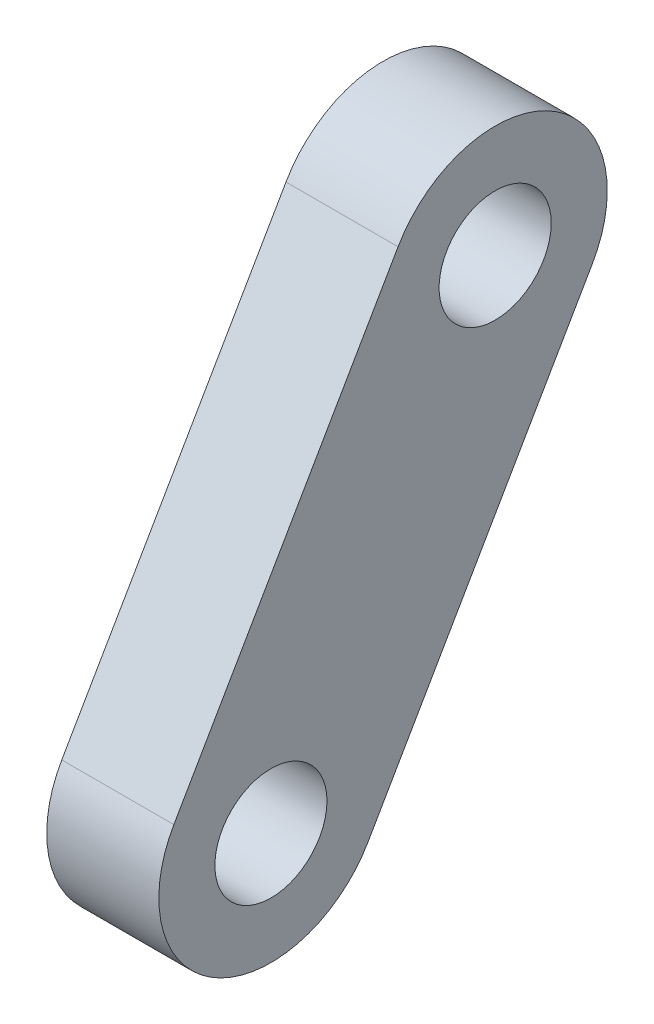
SolidWorks part; units mm, degrees
ref_plane "Front Plane" through (0, 0, 0) normal (0, 0, 1) x (1, 0, 0)
ref_plane "Top Plane" through (0, 0, 0) normal (0, 1, 0) x (1, 0, 0)
ref_plane "Right Plane" through (0, 0, 0) normal (1, 0, 0) x (0, 0, -1)
sketch "Sketch1" plane through (0, 0, 0) normal (1, 0, 0) x (0, 0, -1)
  line L0 (0, 0) -> (103.1479, 0) construction
  line L1 (0, 0) -> (10, 17.3205) construction
  line L2 (-4.3301, 2.5) -> (5.6699, 19.8205)
  line L3 (4.3301, -2.5) -> (14.3301, 14.8205)
  circle A0 centre (0, 0) radius 2.5
  circle A1 centre (10, 17.3205) radius 2.5
  circle A2 centre (0, 0) radius 5
  circle A3 centre (10, 17.3205) radius 5
  dimension "D3" = 5
  dimension "D4" = 5
  dimension "D5" = 10
  dimension "D6" = 10
  dimension "D1" = 60
  dimension "D2" = 20
  dimension "D7" = 20
extrude "Boss-Extrude1" add sketch "Sketch1" along normal blind 5 contours A3 L2 A2 L3 | A3 A1 | A2 A0
